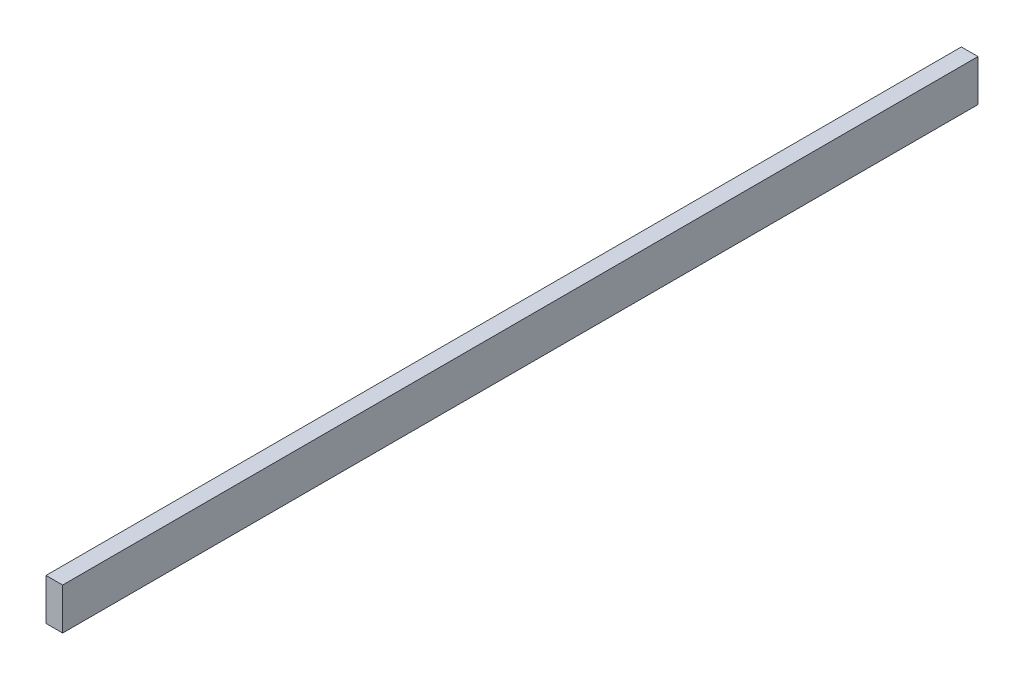
SolidWorks part; units mm, degrees
ref_plane "Front Plane" through (0, 0, 0) normal (0, 0, 1) x (1, 0, 0)
ref_plane "Top Plane" through (0, 0, 0) normal (0, 1, 0) x (1, 0, 0)
ref_plane "Right Plane" through (0, 0, 0) normal (1, 0, 0) x (0, 0, -1)
sketch "Sketch2" plane through (0, 0, 0) normal (1, 0, 0) x (0, 0, -1)
  line L1 (0, 0) -> (550, 0)
  line L2 (0, 0) -> (0, 25)
  line L3 (0, 25) -> (550, 25)
  line L4 (550, 0) -> (550, 25)
extrude "Boss-Extrude1" add sketch "Sketch2" along normal blind 10
